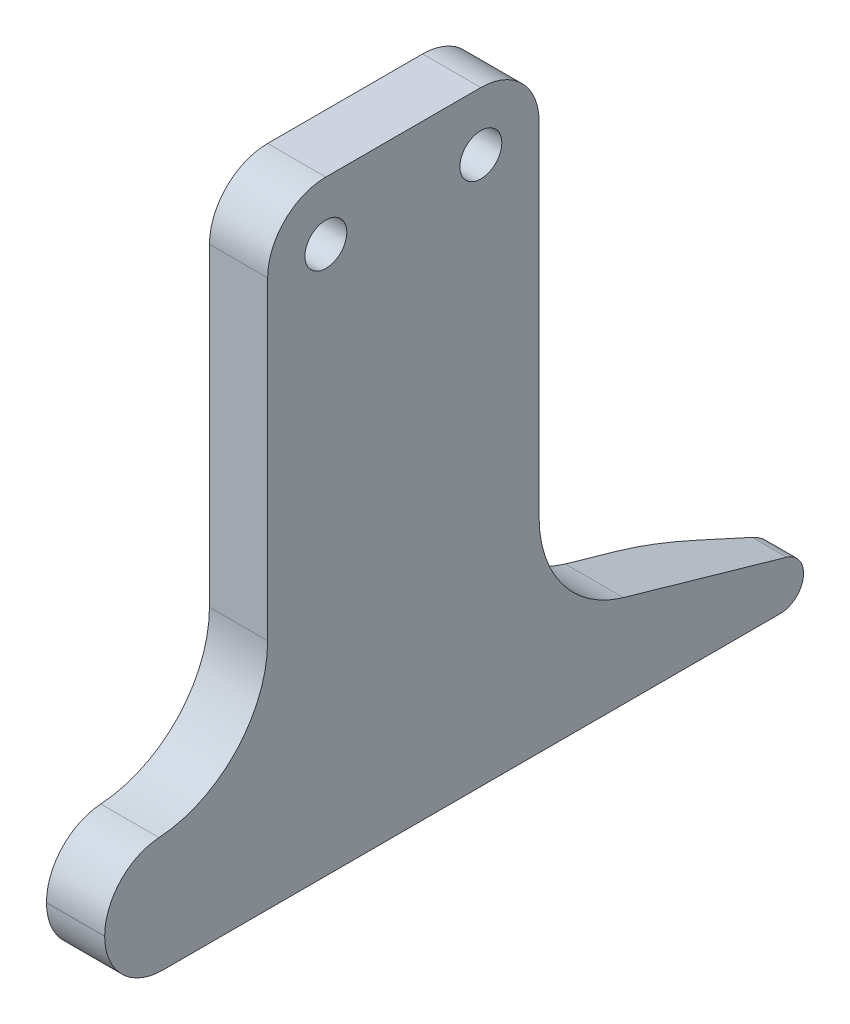
SolidWorks part; units mm, degrees
ref_plane "Front Plane" through (0, 0, 0) normal (0, 0, 1) x (1, 0, 0)
ref_plane "Top Plane" through (0, 0, 0) normal (0, 1, 0) x (1, 0, 0)
ref_plane "Right Plane" through (0, 0, 0) normal (1, 0, 0) x (0, 0, -1)
sketch "Sketch1" plane through (0, 0, 0) normal (1, 0, 0) x (0, 0, -1)
  line L0 (-6.35, 6.35) -> (-6.35, -46.99)
  line L1 (-24.13, -59.69) -> (67.7118, -59.69)
  line L3 (67.7118, -59.69) -> (23.2618, -46.99)
  line L4 (23.2618, -46.99) -> (23.2618, 6.35)
  line L5 (23.2618, 6.35) -> (-6.35, 6.35)
  line L6 (-6.35, -46.99) -> (-24.13, -46.99)
  line L7 (-24.13, -46.99) -> (-24.13, -59.69)
  circle A0 centre (0, 0) radius 2.286
  circle A1 centre (16.9118, 0) radius 2.286
  point P6 (0, 0)
  point P14 (-25.6606, -56.8036)
  point P15 (-24.1507, -59.69)
  point P16 (0, 0)
  point P17 (51.2018, -58.8527)
  dimension "D1" = 4.572
  dimension "D2" = 4.572
  dimension "D3" = 6.35
  dimension "D4" = 6.35
  dimension "D5" = 6.35
  dimension "D6" = 16.9118
  dimension "D7" = 66.04
  dimension "D8" = 12.7
  dimension "D9" = 44.45
  dimension "D10" = 17.78
extrude "Boss-Extrude1" add sketch "Sketch1" along normal blind 6.35
fillet "Fillet1" radius 12.7 2 edges at (3.175, -46.99, -23.2618) (3.175, -46.99, 6.35)
fillet "Fillet2" radius 6.35 4 edges at (3.175, 6.35, 6.35) (3.175, 6.35, -23.2618) (3.175, -59.69, 24.13) (3.175, -46.99, 24.13)
fillet "Fillet3" radius 2.54 1 edges at (3.175, -59.69, -67.7118)
sketch "Sketch2" plane through (0, -59.69, 0) normal (0, -1, 0) x (1, 0, 0)
  line L0 (0, -41.9561) -> (3.175, -52.1161)
  line L1 (0, 17.78) -> (0, -49.5761) construction
  line L2 (0, -52.1161) -> (6.35, -52.1161) construction
  line L3 (3.175, -52.1161) -> (0, -52.1161)
  line L4 (0, -52.1161) -> (0, -41.9561)
  dimension "D1" = 10.16
extrude "Cut-Extrude1" cut sketch "Sketch2" against normal through all
fillet "Fillet4" radius 25.4 1 edges at (0, -56.0106, -41.9561)
